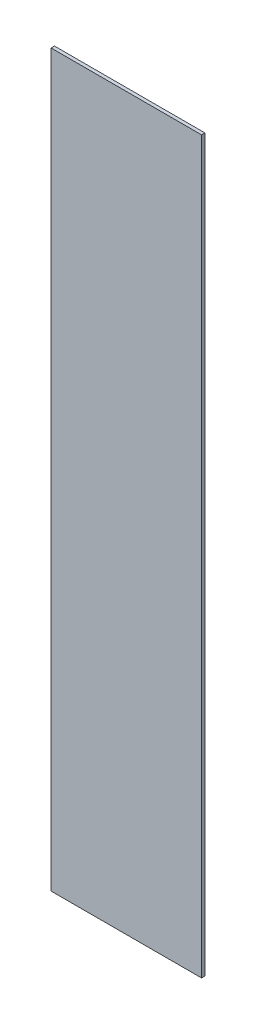
SolidWorks part; units mm, degrees
material "Chapa F.F 1020 - 1,5 mm"
ref_plane "Plano frontal" through (0, 0, 0) normal (0, 0, 1) x (1, 0, 0)
ref_plane "Plano superior" through (0, 0, 0) normal (0, 1, 0) x (1, 0, 0)
ref_plane "Plano direito" through (0, 0, 0) normal (1, 0, 0) x (0, 0, -1)
sketch "Esboço1" plane through (0, 0, 0) normal (0, 0, 1) x (1, 0, 0)
  line L1 (-33.5, -162.5) -> (33.5, -162.5)
  line L2 (-33.5, -162.5) -> (-33.5, 162.5)
  line L3 (-33.5, 162.5) -> (33.5, 162.5)
  line L4 (33.5, -162.5) -> (33.5, 162.5)
  line L5 (-33.5, -162.5) -> (33.5, 162.5) construction
  line L6 (-33.5, 162.5) -> (33.5, -162.5) construction
  point P0 (0, 0)
  dimension "D1" = 325
  dimension "D2" = 67
extrude "Ressalto-extrusão1" add sketch "Esboço1" along normal blind 1.5
